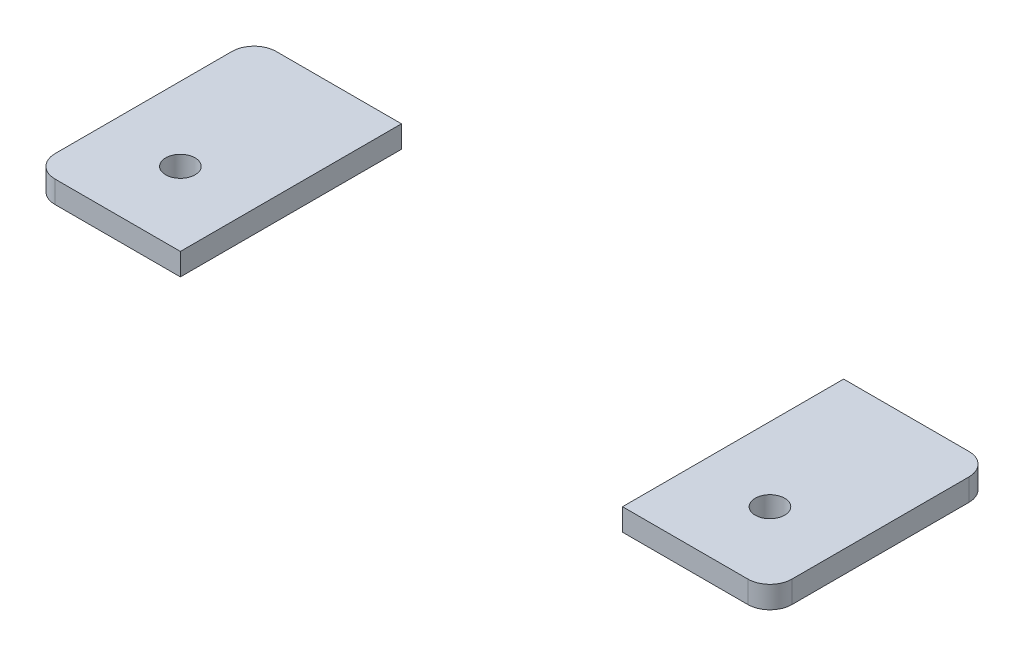
SolidWorks part; units mm, degrees
ref_plane "前视基准面" through (0, 0, 0) normal (0, 0, 1) x (1, 0, 0)
ref_plane "上视基准面" through (0, 0, 0) normal (0, 1, 0) x (1, 0, 0)
ref_plane "右视基准面" through (0, 0, 0) normal (1, 0, 0) x (0, 0, -1)
other "Configuration Table"
sketch "草图1" plane through (0, 0, 0) normal (0, 1, 0) x (1, 0, 0)
  line L0 (-30, 15) -> (-30, -15)
  line L1 (-47, -15) -> (-30, -15)
  line L2 (-50, -12) -> (-50, 12)
  line L3 (-47, 15) -> (-30, 15)
  line L4 (50, -12) -> (50, 12)
  line L5 (-50, -15) -> (50, 15) construction
  line L6 (-50, 15) -> (50, -15) construction
  line L7 (30, 15) -> (30, -15)
  line L8 (30, 15) -> (47, 15)
  line L9 (30, -15) -> (47, -15)
  arc A0 (47, -15) -> (50, -12) centre (47, -12) ccw
  arc A1 (-50, 12) -> (-47, 15) centre (-47, 12) cw
  arc A2 (-47, -15) -> (-50, -12) centre (-47, -12) cw
  arc A3 (47, 15) -> (50, 12) centre (47, 12) cw
  circle A4 centre (-40, -5) radius 2
  circle A5 centre (40, -5) radius 2
  point P0 (0, 0)
  dimension "D3" = 3
  dimension "D6" = 4
  dimension "D7" = 4
  dimension "D1" = 30
  dimension "D2" = 100
  dimension "D4" = 10
  dimension "D5" = 10
  dimension "D8" = 30
  dimension "D9" = 30
  dimension "D10" = 10
  dimension "D11" = 10
extrude "凸台-拉伸2" add sketch "草图1" along normal blind 3 contours A2 L1 L0 L3 A1 L2 A4 | A5 | L4 A3 L8 L7 L9 A0
